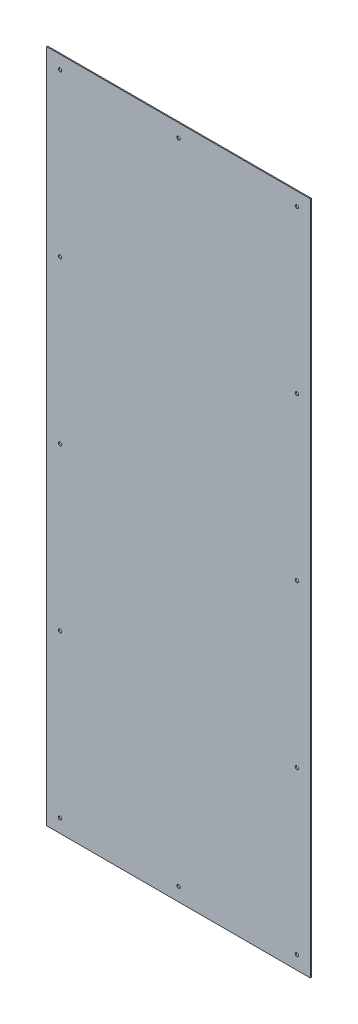
SolidWorks part; units mm, degrees
ref_plane "Alzado" through (0, 0, 0) normal (0, 0, 1) x (1, 0, 0)
ref_plane "Planta" through (0, 0, 0) normal (0, 1, 0) x (1, 0, 0)
ref_plane "Vista lateral" through (0, 0, 0) normal (1, 0, 0) x (0, 0, -1)
sketch "Croquis1" plane through (0, 0, 0) normal (0, 0, 1) x (1, 0, 0)
  line L1 (-250, 640) -> (250, 640)
  line L2 (-250, 640) -> (-250, -640)
  line L3 (-250, -640) -> (250, -640)
  line L4 (250, 640) -> (250, -640)
  line L5 (-250, 640) -> (250, -640) construction
  line L6 (-250, -640) -> (250, 640) construction
  point P0 (0, 0)
  dimension "D1" = 500
  dimension "D2" = 1280
extrude "Saliente-Extruir1" add sketch "Croquis1" along normal blind 1.9
sketch "Croquis2" plane through (0, 0, 1.9) normal (0, 0, 1) x (1, 0, 0)
  line L0 (-250, 640) -> (-250, -640) construction
  line L1 (-224.6, -614.6) -> (224.6, -614.6) construction
  line L2 (-224.6, -614.6) -> (-224.6, 614.6) construction
  line L3 (-224.6, 614.6) -> (224.6, 614.6) construction
  line L4 (224.6, -614.6) -> (224.6, 614.6) construction
  line L5 (-224.6, -614.6) -> (224.6, 614.6) construction
  line L6 (-224.6, 614.6) -> (224.6, -614.6) construction
  line L7 (250, 640) -> (-250, 640) construction
  line L8 (-224.6, 0) -> (224.6, 0) construction
  line L9 (0, 0) -> (0, -614.6) construction
  line L10 (0, 0) -> (0, 614.6) construction
  line L11 (-224.6, 0) -> (-224.6, 614.6) construction
  line L12 (-224.6, 614.6) -> (-224.6, 307.3) construction
  line L13 (-224.6, 307.3) -> (224.6, 307.3) construction
  line L14 (-224.6, 0) -> (-224.6, -614.6) construction
  line L15 (-224.6, -614.6) -> (-224.6, -307.3) construction
  line L16 (-224.6, -307.3) -> (224.6, -307.3) construction
  circle A0 centre (-224.6, 614.6) radius 3.175
  circle A1 centre (224.6, 614.6) radius 3.175
  circle A2 centre (0, 614.6) radius 3.175
  circle A3 centre (224.6, -614.6) radius 3.175
  circle A4 centre (0, -614.6) radius 3.175
  circle A5 centre (-224.6, -614.6) radius 3.175
  circle A6 centre (-224.6, 0) radius 3.175
  circle A7 centre (224.6, 0) radius 3.175
  circle A8 centre (-224.6, 307.3) radius 3.175
  circle A9 centre (224.6, 307.3) radius 3.175
  circle A10 centre (-224.6, -307.3) radius 3.175
  circle A11 centre (224.6, -307.3) radius 3.175
  point P0 (0, 0)
  dimension "D3" = 6.35
  dimension "D4" = 6.35
  dimension "D5" = 6.35
  dimension "D6" = 6.35
  dimension "D7" = 6.35
  dimension "D8" = 6.35
  dimension "D9" = 6.35
  dimension "D1" = 25.4
  dimension "D2" = 25.4
extrude "Cortar-Extruir1" cut sketch "Croquis2" against normal blind 10
